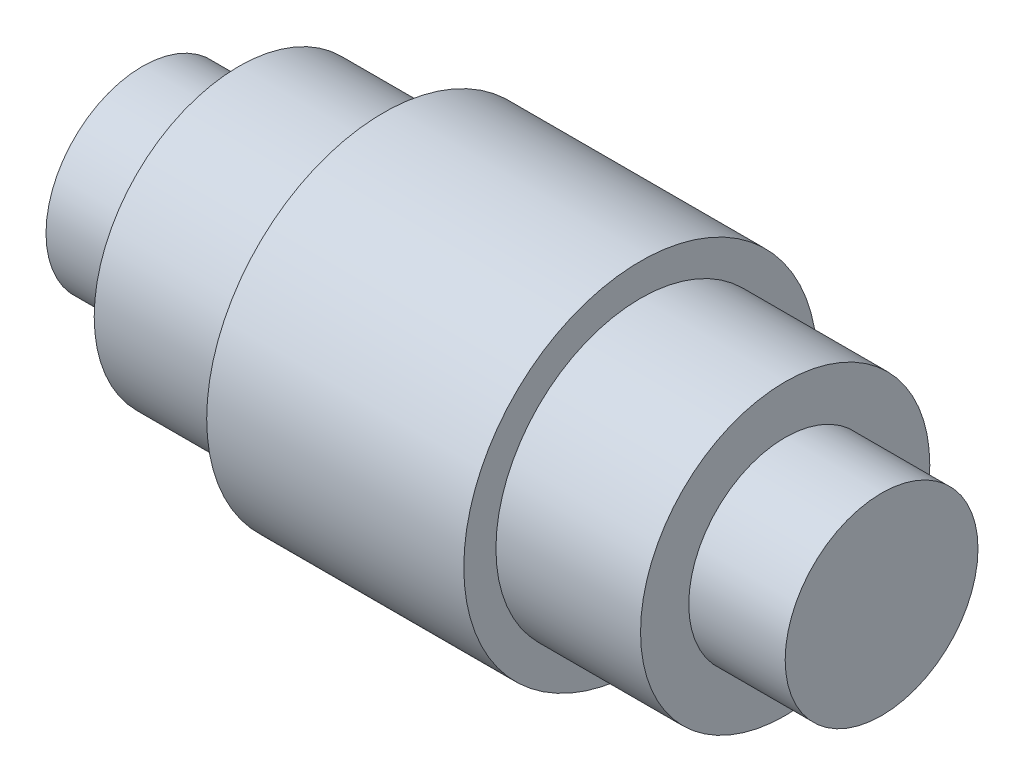
SolidWorks part; units mm, degrees
ref_plane "Plano frontal" through (0, 0, 0) normal (0, 0, 1) x (1, 0, 0)
ref_plane "Plano superior" through (0, 0, 0) normal (0, 1, 0) x (1, 0, 0)
ref_plane "Plano direito" through (0, 0, 0) normal (1, 0, 0) x (0, 0, -1)
sketch "Esboço1" plane through (0, 0, 0) normal (0, 0, 1) x (1, 0, 0)
  line L0 (0, 0) -> (230, 0)
  line L1 (0, 0) -> (0, 30)
  line L2 (0, 30) -> (30, 30)
  line L3 (30, 30) -> (30, 45)
  line L4 (30, 45) -> (75, 45)
  line L5 (75, 45) -> (75, 55)
  line L6 (75, 55) -> (155, 55)
  line L13 (155, 45) -> (155, 55)
  line L14 (200, 45) -> (155, 45)
  line L15 (200, 30) -> (200, 45)
  line L16 (230, 30) -> (200, 30)
  line L17 (230, 0) -> (230, 30)
  point P3 (0, 0)
  point P16 (115, 0)
  dimension "D2" = 30
  dimension "D3" = 45
  dimension "D6" = 30
  dimension "D7" = 45
  dimension "D8" = 55
revolve "Revolução1" add sketch "Esboço1" angle 360 about L0
